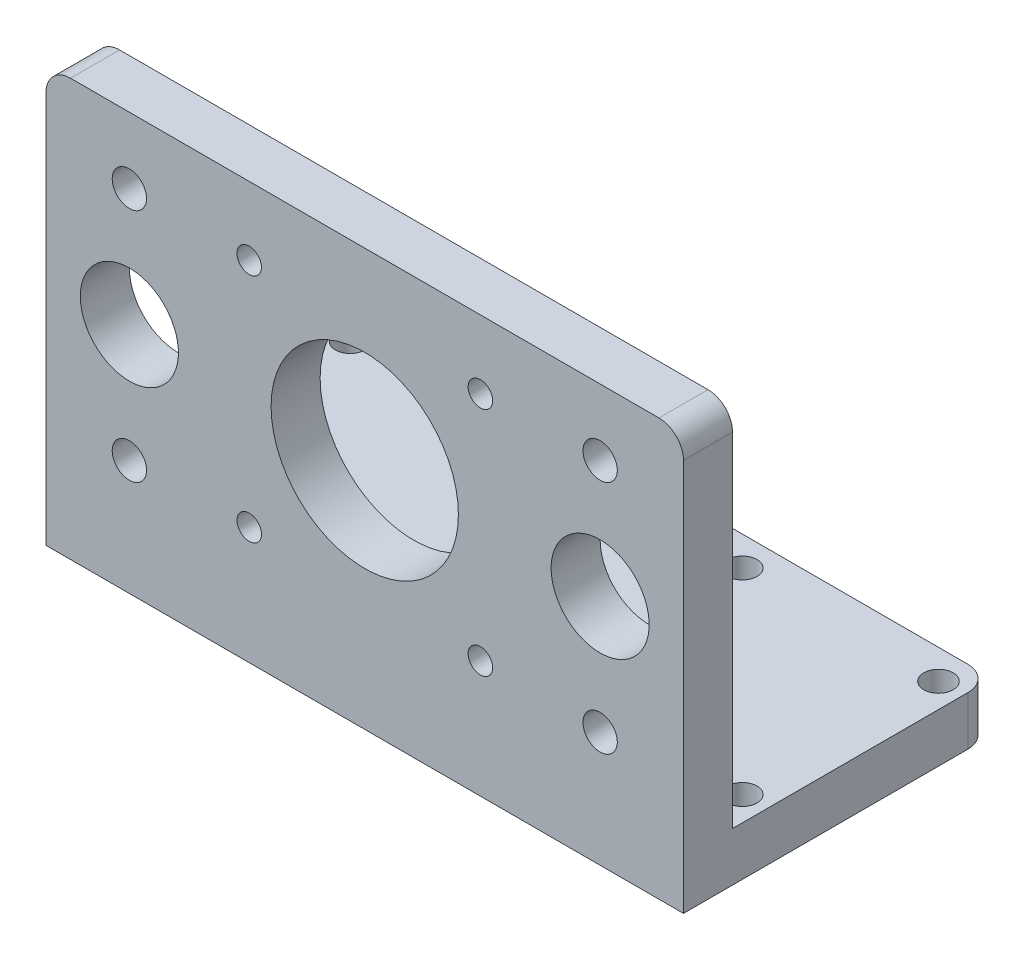
SolidWorks part; units mm, degrees
ref_plane "Front Plane" through (0, 0, 0) normal (0, 0, 1) x (1, 0, 0)
ref_plane "Top Plane" through (0, 0, 0) normal (0, 1, 0) x (1, 0, 0)
ref_plane "Right Plane" through (0, 0, 0) normal (1, 0, 0) x (0, 0, -1)
sketch "Sketch1" plane through (0, 0, 0) normal (0, 1, 0) x (1, 0, 0)
  line L0 (0, 0) -> (5, 0)
  line L1 (0, 0) -> (130, 0)
  line L2 (0, 0) -> (0, 63)
  line L3 (0, 63) -> (130, 63)
  line L4 (130, 0) -> (130, 63)
  line L5 (0, 0) -> (0, -37)
  line L6 (0, -37) -> (130, -37)
  line L7 (130, -37) -> (130, 0)
  line L9 (0, -37) -> (130, -37)
  line L10 (0, -37) -> (0, -27)
  line L11 (0, -27) -> (130, -27)
  line L12 (130, -37) -> (130, -27)
  circle A0 centre (5, 57) radius 3
  circle A1 centre (45, 57) radius 3
  circle A2 centre (5, 17) radius 3
  circle A3 centre (45, 17) radius 3
  circle A4 centre (85, 57) radius 3
  circle A5 centre (125, 57) radius 3
  circle A6 centre (85, 17) radius 3
  circle A7 centre (125, 17) radius 3
  dimension "D1" = 10
extrude "Boss-Extrude1" add sketch "Sketch1" along normal blind 10 contours L1 L4 L3 L2 L0 A7 A6 A5 A4 A3 A2 A1 A0 | L5 L11 L7 L1 L0 | L11 L5 L6 L7
sketch "Sketch2" plane through (0, 10, 0) normal (0, 1, 0) x (1, 0, 0)
  line L0 (130, -37) -> (130, 63) construction
  line L1 (0, -37) -> (130, -37)
  line L2 (0, -37) -> (0, -28.977)
  line L3 (0, -28.977) -> (130, -28.977)
  line L4 (130, -37) -> (130, -28.977)
extrude "Boss-Extrude2" add sketch "Sketch2" along normal blind 75
fillet "Fillet1" radius 5 4 edges at (0, 85, 32.9885) (130, 85, 32.9885) (130, 5, -63) (0, 5, -63)
sketch "Sketch3" plane through (0, 85, 0) normal (0, 1, 0) x (1, 0, 0)
  line L0 (130, -28.977) -> (125, -28.977) construction
  line L1 (0, -37) -> (130, -37)
  line L2 (0, -37) -> (0, -28.977)
  line L3 (0, -28.977) -> (130, -28.977)
  line L4 (130, -37) -> (130, -28.977)
  line L5 (130, -28.977) -> (130, -37) construction
extrude "Cut-Extrude1" cut sketch "Sketch3" against normal blind 75
sketch "Sketch4" plane through (0, 0, 37) normal (0, 0, 1) x (1, 0, 0)
  line L1 (0, 0) -> (130, 0)
  line L2 (0, 0) -> (0, 10)
  line L3 (0, 10) -> (130, 10)
  line L4 (130, 0) -> (130, 10)
extrude "Cut-Extrude2" cut sketch "Sketch4" against normal blind 37
sketch "Sketch5" plane through (0, 10, 0) normal (0, 1, 0) x (1, 0, 0)
  line L0 (130, 0) -> (130, 58) construction
  line L1 (0, 0) -> (130, 0)
  line L2 (0, 0) -> (0, 10)
  line L3 (0, 10) -> (130, 10)
  line L4 (130, 0) -> (130, 10)
  dimension "D1" = 10
extrude "Boss-Extrude4" add sketch "Sketch5" along normal blind 75
fillet "Fillet2" radius 5 2 edges at (130, 85, -5) (0, 85, -5)
sketch "Sketch6" plane through (0, 0, -10) normal (0, 0, -1) x (-1, 0, 0)
  circle A0 centre (-113, 47.5) radius 10
  circle A1 centre (-65, 47.5) radius 7.5
  circle A2 centre (-17, 47.5) radius 10
  circle A3 centre (-113, 71.5) radius 3.5
  circle A4 centre (-65, 74.04) radius 3.5
  circle A5 centre (-17, 71.5) radius 3.5
  circle A6 centre (-17, 23.5) radius 3.5
  circle A7 centre (-65, 21) radius 3.5
  circle A8 centre (-113, 23.5) radius 3.5
  circle A9 centre (-88.58, 71.06) radius 2.5
  circle A10 centre (-41.44, 71.06) radius 2.5
  circle A11 centre (-41.44, 23.92) radius 2.5
  circle A12 centre (-88.58, 23.92) radius 2.5
extrude "Cut-Extrude3" cut sketch "Sketch6" against normal blind 10
sketch "Sketch7" plane through (0, 0, -10) normal (0, 0, -1) x (-1, 0, 0)
  circle A0 centre (-65, 47.5) radius 19.1
extrude "Cut-Extrude4" cut sketch "Sketch7" against normal blind 10
sketch "Sketch8" plane through (0, 0, -10) normal (0, 0, -1) x (-1, 0, 0)
  circle A0 centre (-65, 74.04) radius 3.5
  circle A1 centre (-65, 21) radius 3.5
extrude "Boss-Extrude5" add sketch "Sketch8" against normal blind 10
